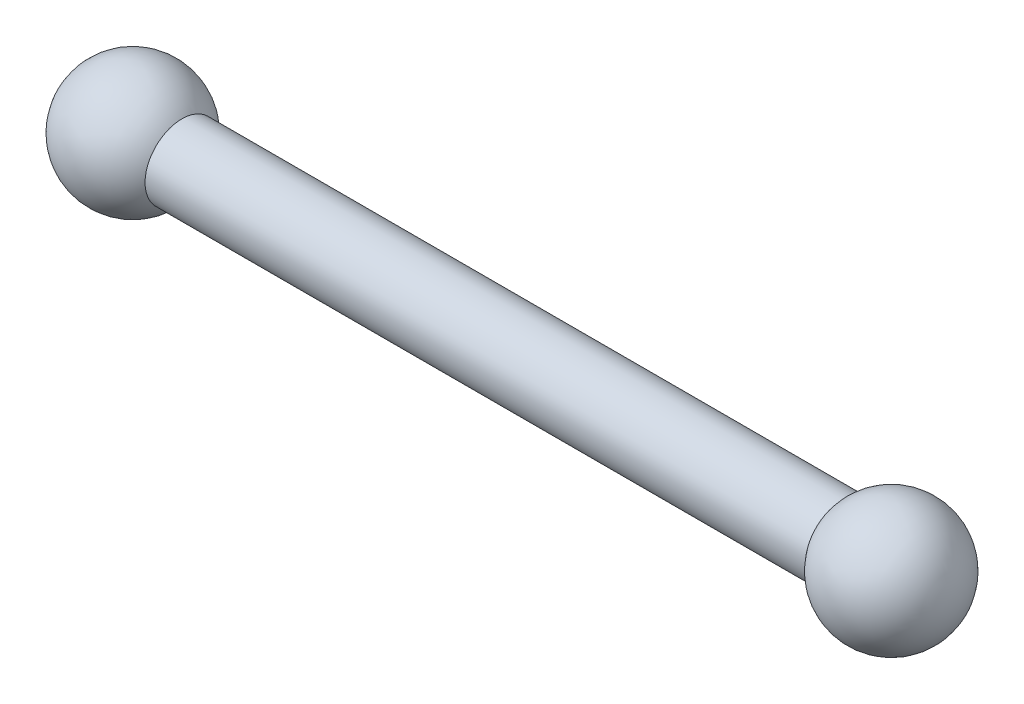
SolidWorks part; units mm, degrees
ref_plane "Front Plane" through (0, 0, 0) normal (0, 0, 1) x (1, 0, 0)
ref_plane "Top Plane" through (0, 0, 0) normal (0, 1, 0) x (1, 0, 0)
ref_plane "Right Plane" through (0, 0, 0) normal (1, 0, 0) x (0, 0, -1)
sketch "Sketch4" plane through (0, 0, 0) normal (1, 0, 0) x (0, 0, -1)
  line L0 (0, 0) -> (2.5, 0)
  line L1 (2.5, 0) -> (2.5, -2.5)
  arc A0 (0, 0) -> (2.5, -2.5) centre (2.5, 0) ccw
  dimension "D3" = 2.5
  dimension "D1" = 2.5
  dimension "D2" = 2.5
revolve "Semi-circle Revolve" add sketch "Sketch4" angle 360 about L1
mirror "Full-circle Mirror" about plane through (0, 0, 0) normal (0, -1, 0) of "Semi-circle Revolve"
sketch "Sketch5" plane through (0, 0, 0) normal (1, 0, 0) x (0, 0, -1)
  line L0 (0, 0) -> (2.5, 0) construction
  circle A0 centre (2.5, 0) radius 1.5
  dimension "D2" = 3
  dimension "D1" = 2.5
extrude "Shaft" add sketch "Sketch5" along normal blind 30.9
sketch "Sketch6" plane through (30.9, 0, 0) normal (1, 0, 0) x (0, 0, -1)
  line L0 (0, 0) -> (2.5, 0)
  line L1 (2.5, 0) -> (2.5, -2.5)
  arc A0 (0, 0) -> (2.5, -2.5) centre (2.5, 0) ccw
  dimension "D1" = 2.5
  dimension "D2" = 2.5
revolve "Opposite Semi-circle Revolve" add sketch "Sketch6" angle 360 about L1
mirror "Opposite Full-circle Mirror" about plane through (30.9, 0, 0) normal (0, 1, 0) of "Opposite Semi-circle Revolve"
